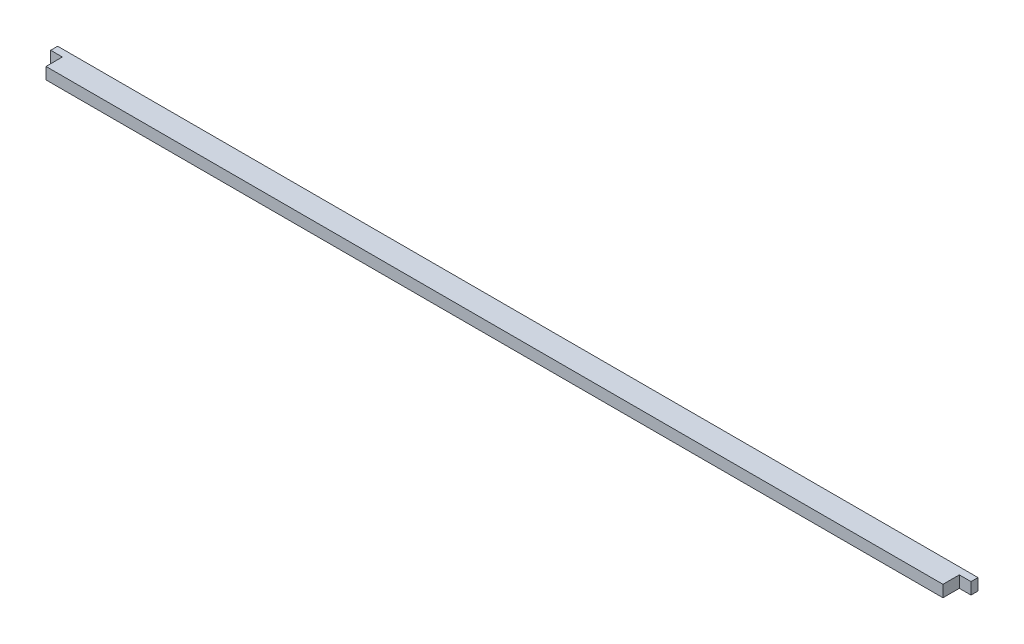
SolidWorks part; units mm, degrees
ref_plane "Płaszczyzna przednia" through (0, 0, 0) normal (0, 0, 1) x (1, 0, 0)
ref_plane "Płaszczyzna górna" through (0, 0, 0) normal (0, 1, 0) x (1, 0, 0)
ref_plane "Płaszczyzna prawa" through (0, 0, 0) normal (1, 0, 0) x (0, 0, -1)
sketch "Szkic1" plane through (0, 0, 0) normal (0, 1, 0) x (1, 0, 0)
  line L1 (-218.9484, -72.7079) -> (175.0516, -72.7079)
  line L2 (-218.9484, -72.7079) -> (-218.9484, -82.7079)
  line L3 (-218.9484, -82.7079) -> (175.0516, -82.7079)
  line L4 (175.0516, -72.7079) -> (175.0516, -82.7079)
  dimension "D1" = 394
  dimension "D2" = 10
extrude "Dodanie-wyciągnięcie1" add sketch "Szkic1" along normal blind 5
sketch "Szkic2" plane through (0, 5, 0) normal (0, 1, 0) x (1, 0, 0)
  line L0 (-218.9484, -72.7079) -> (-218.9484, -82.7079) construction
  line L1 (-218.9484, -82.7079) -> (-213.9484, -82.7079)
  line L2 (-218.9484, -82.7079) -> (-218.9484, -75.7079)
  line L3 (-218.9484, -75.7079) -> (-213.9484, -75.7079)
  line L4 (-213.9484, -82.7079) -> (-213.9484, -75.7079)
  line L5 (-218.9484, -82.7079) -> (175.0516, -82.7079) construction
  line L7 (175.0516, -82.7079) -> (170.0516, -82.7079)
  line L8 (175.0516, -82.7079) -> (175.0516, -75.7079)
  line L9 (175.0516, -75.7079) -> (170.0516, -75.7079)
  line L10 (170.0516, -82.7079) -> (170.0516, -75.7079)
  dimension "D1" = 5
  dimension "D2" = 7
  dimension "D3" = 5
  dimension "D4" = 7
extrude "Wytnij-wyciągnięcie1" cut sketch "Szkic2" against normal blind 5
